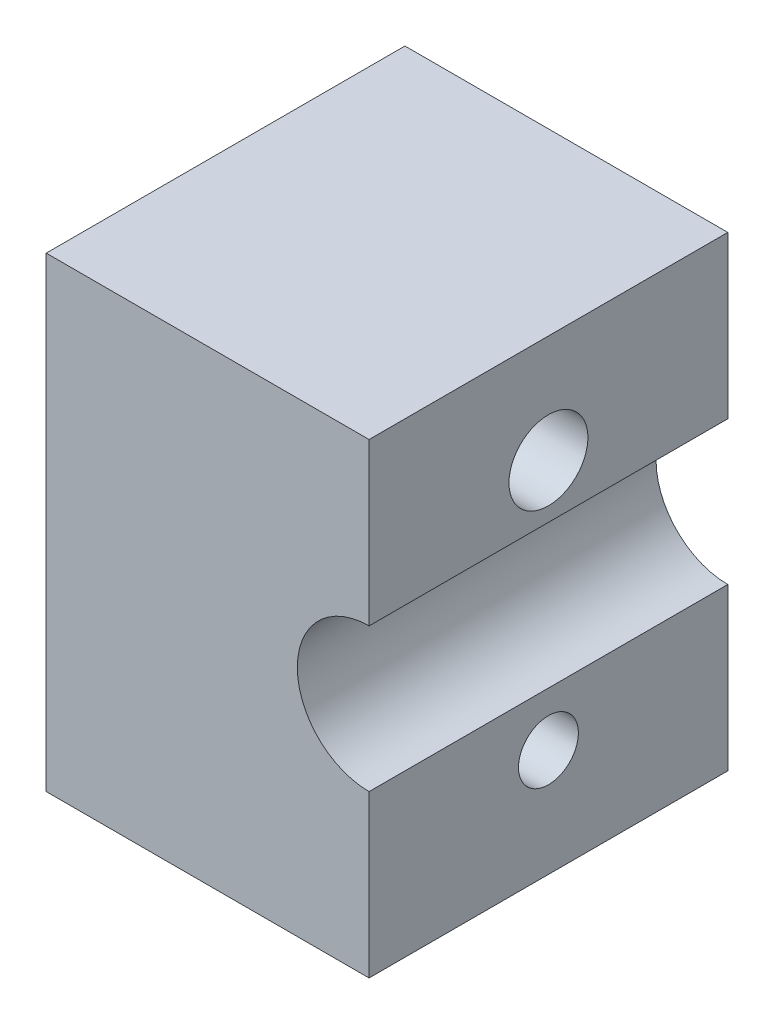
SolidWorks part; units mm, degrees
ref_plane "Front Plane" through (0, 0, 0) normal (0, 0, 1) x (1, 0, 0)
ref_plane "Top Plane" through (0, 0, 0) normal (0, 1, 0) x (1, 0, 0)
ref_plane "Right Plane" through (0, 0, 0) normal (1, 0, 0) x (0, 0, -1)
ref_plane "Plane1" through (-47, 0, 0) normal (-1, 0, 0) x (0, -1, 0)
sketch "Sketch1" plane through (-47, 0, 0) normal (-1, 0, 0) x (0, -1, 0)
  line L0 (13, 18) -> (-13, 18)
  line L1 (-13, 18) -> (-13, -2)
  line L2 (-13, -2) -> (13, -2)
  line L3 (13, -2) -> (13, 18)
extrude "Boss-Extrude1" add sketch "Sketch1" against normal blind 18
hole_wizard "Hole1" positions "Sketch3" profile "Sketch2" legacy
sketch "Sketch3" plane through (-47, 0, 0) normal (-1, 0, 0) x (0, 0, 1)
  point P0 (8, 7)
sketch "Sketch2" plane through (-47, 7, 8) normal (0, 1, 0) x (0, 0, 1)
  line L0 (0, 0) -> (0, 18)
  line L1 (0, 18) -> (2.2, 18)
  line L2 (2.2, 18) -> (2.2, 0)
  line L3 (2.2, 0) -> (0, 0)
  line L4 (0, 110) -> (0, -10) construction
  dimension "Diameter" = 4.4
  dimension "Depth" = 18
hole_wizard "Hole2" positions "Sketch5" profile "Sketch4" legacy
sketch "Sketch5" plane through (-47, 0, 0) normal (-1, 0, 0) x (0, 0, 1)
  point P0 (8, -7)
sketch "Sketch4" plane through (-47, -7, 8) normal (0, 1, 0) x (0, 0, 1)
  line L0 (0, 0) -> (0, 18)
  line L1 (0, 18) -> (1.6692, 18)
  line L2 (1.6692, 18) -> (1.6692, 0)
  line L3 (1.6692, 0) -> (0, 0)
  line L4 (0, 110) -> (0, -10) construction
  dimension "Diameter" = 3.3384
  dimension "Depth" = 18
hole_wizard "Hole3" positions "Sketch7" profile "Sketch6" legacy
sketch "Sketch7" plane through (0, 0, -2) normal (0, 0, -1) x (-1, 0, 0)
  point P0 (29, 0)
sketch "Sketch6" plane through (-29, 0, -2) normal (1, 0, 0) x (0, 1, 0)
  line L0 (0, 0) -> (0, 20)
  line L1 (0, 20) -> (4, 20)
  line L2 (4, 20) -> (4, 0)
  line L3 (4, 0) -> (0, 0)
  line L4 (0, 110) -> (0, -10) construction
  dimension "Diameter" = 8
  dimension "Depth" = 20
